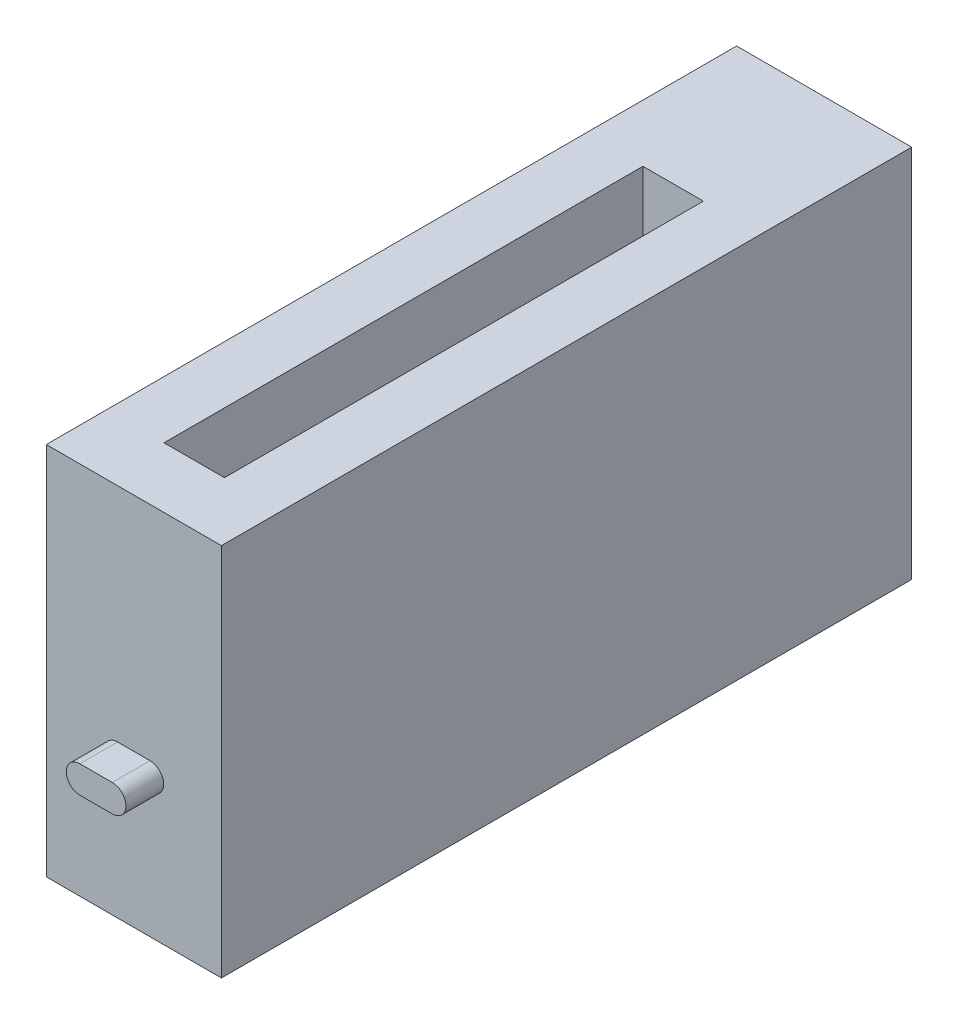
SolidWorks part; units mm, degrees
ref_plane "Front Plane" through (0, 0, 0) normal (0, 0, 1) x (1, 0, 0)
ref_plane "Top Plane" through (0, 0, 0) normal (0, 1, 0) x (1, 0, 0)
ref_plane "Right Plane" through (0, 0, 0) normal (1, 0, 0) x (0, 0, -1)
sketch "Sketch1" plane through (0, 0, 0) normal (0, 1, 0) x (1, 0, 0)
  line L1 (-3.683, -14.5161) -> (3.683, -14.5161)
  line L2 (-3.683, -14.5161) -> (-3.683, 14.5161)
  line L3 (-3.683, 14.5161) -> (3.683, 14.5161)
  line L4 (3.683, -14.5161) -> (3.683, 14.5161)
  line L5 (-3.683, -14.5161) -> (3.683, 14.5161) construction
  line L6 (-3.683, 14.5161) -> (3.683, -14.5161) construction
  point P0 (0, 0)
  dimension "D1" = 7.366
  dimension "D2" = 29.0322
extrude "Boss-Extrude1" add sketch "Sketch1" along normal blind 15.748
sketch "Sketch2" plane through (0, 15.748, 0) normal (0, 1, 0) x (1, 0, 0)
  line L0 (0, -1.905) -> (0, 0) construction
  line L1 (-1.27, -11.9761) -> (1.27, -11.9761)
  line L2 (-1.27, -11.9761) -> (-1.27, 8.1661)
  line L3 (-1.27, 8.1661) -> (1.27, 8.1661)
  line L4 (1.27, -11.9761) -> (1.27, 8.1661)
  line L5 (-1.27, -11.9761) -> (1.27, 8.1661) construction
  line L6 (-1.27, 8.1661) -> (1.27, -11.9761) construction
  line L7 (3.683, 14.5161) -> (-3.683, 14.5161) construction
  line L8 (-3.683, -14.5161) -> (3.683, -14.5161) construction
  point P0 (0, -1.905)
  dimension "D1" = 6.35
  dimension "D2" = 2.54
  dimension "D3" = 2.54
extrude "Cut-Extrude1" cut sketch "Sketch2" against normal blind 3.175
sketch "Sketch5" plane through (0, 0, 14.5161) normal (0, 0, 1) x (1, 0, 0)
  line L1 (-0.6827, 5.842) -> (0.6827, 5.842) construction
  line L2 (-0.6827, 6.414) -> (0.6827, 6.414)
  line L3 (-0.6827, 5.27) -> (0.6827, 5.27)
  line L4 (-3.683, 0) -> (3.683, 0) construction
  arc A1 (-0.6827, 6.414) -> (-0.6827, 5.27) centre (-0.6827, 5.842) ccw
  arc A2 (0.6827, 5.27) -> (0.6827, 6.414) centre (0.6827, 5.842) ccw
  point P6 (0, 5.842)
  dimension "D1" = 5.842
extrude "Boss-Extrude3" add sketch "Sketch5" along normal blind 1.5875
